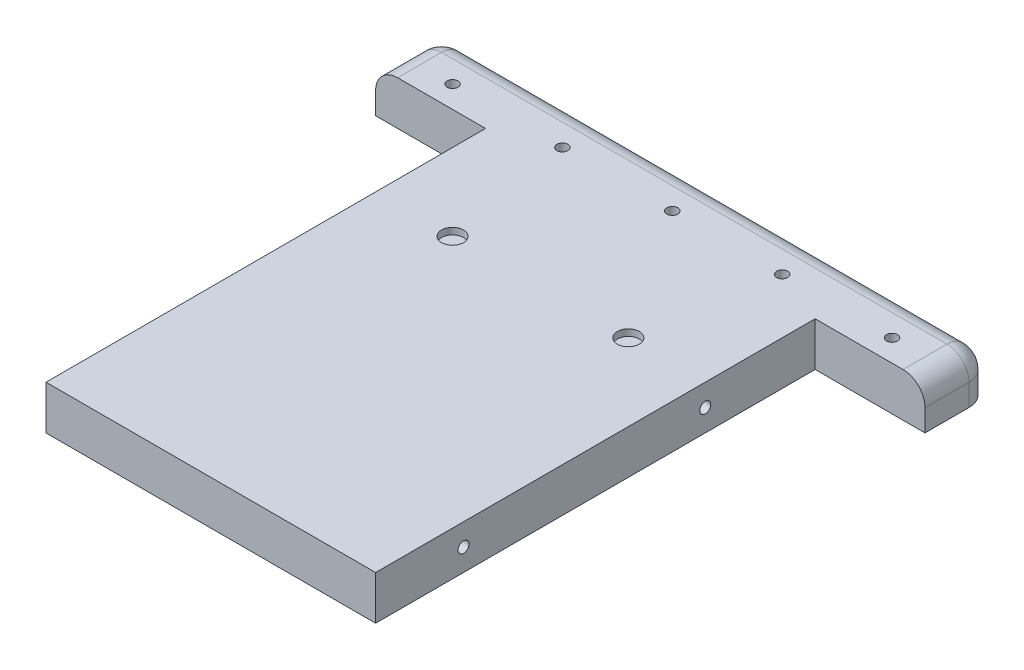
SolidWorks part; units mm, degrees
ref_plane "Front Plane" through (0, 0, 0) normal (0, 0, 1) x (1, 0, 0)
ref_plane "Top Plane" through (0, 0, 0) normal (0, 1, 0) x (1, 0, 0)
ref_plane "Right Plane" through (0, 0, 0) normal (1, 0, 0) x (0, 0, -1)
sketch "Sketch1" plane through (0, 0, 0) normal (0, 1, 0) x (1, 0, 0)
  line L0 (-75, -100) -> (75, -100)
  line L1 (75, -100) -> (75, 100)
  line L2 (75, 100) -> (125, 100)
  line L3 (125, 100) -> (125, 130)
  line L4 (125, 130) -> (-125, 130)
  line L5 (-125, 130) -> (-125, 100)
  line L6 (-125, 100) -> (-75, 100)
  line L7 (-75, 100) -> (-75, -100)
  point P7 (0, -100)
  point P9 (-75, 0)
  dimension "D1" = 250
  dimension "D2" = 30
  dimension "D3" = 150
  dimension "D4" = 200
extrude "Boss-Extrude1" add sketch "Sketch1" along normal blind 20
sketch "Sketch2" plane through (-75, 0, 0) normal (-1, 0, 0) x (0, 0, 1)
  line L0 (100, 20) -> (100, 0) construction
  circle A0 centre (60, 10) radius 2.5
  circle A1 centre (-50, 10) radius 2.5
  point P6 (100, 10)
  dimension "D1" = 5
  dimension "D2" = 40
  dimension "D3" = 110
extrude "Cut-Extrude1" cut sketch "Sketch2" against normal through all
sketch "Sketch4" plane through (0, 0, 0) normal (0, -1, 0) x (1, 0, 0)
  line L0 (-125, -115) -> (125, -115) construction
  line L1 (-125, -130) -> (-125, -100) construction
  line L2 (125, -100) -> (125, -130) construction
  line L3 (0, -11) -> (0, 11) construction
  circle A0 centre (-100, -115) radius 2.5
  circle A1 centre (-50, -115) radius 2.5
  circle A2 centre (0, -115) radius 2.5
  circle A3 centre (50, -115) radius 2.5
  circle A4 centre (100, -115) radius 2.5
  dimension "D1" = 5
  dimension "D2" = 25
  dimension "D3" = 50
extrude "Cut-Extrude2" cut sketch "Sketch4" against normal blind 5
fillet "Fillet1" radius 10 2 edges at (125, 10, -130) (-125, 10, -130)
fillet "Fillet2" radius 10 5 edges at (125, 20, -110) (122.0711, 20, -127.0711) (-125, 20, -110) (-122.0711, 20, -127.0711) (0, 20, -130)
sketch "Sketch6" plane through (0, 20, 0) normal (0, 1, 0) x (1, 0, 0)
  line L0 (115, 110) -> (-115, 110) construction
  line L1 (115, 100) -> (115, 120) construction
  line L2 (-115, 120) -> (-115, 100) construction
  line L3 (0, -11) -> (0, 11) construction
  circle A0 centre (0, 110) radius 2.5
  circle A1 centre (50, 110) radius 2.5
  circle A2 centre (100, 110) radius 2.5
  circle A3 centre (-50, 110) radius 2.5
  circle A4 centre (-100, 110) radius 2.5
  dimension "D1" = 5
  dimension "D2" = 50
  dimension "D3" = 50
extrude "Cut-Extrude3" cut sketch "Sketch6" against normal blind 5
sketch "Sketch8" plane through (0, 20, 0) normal (0, 1, 0) x (1, 0, 0)
  line L0 (-75, 100) -> (-75, -100) construction
  line L1 (-75, -100) -> (75, -100) construction
  line L2 (0, -11) -> (0, 11) construction
  circle A0 centre (-40, 50) radius 5
  circle A1 centre (40, 50) radius 5
  dimension "D1" = 10
  dimension "D2" = 35
  dimension "D3" = 150
extrude "Cut-Extrude5" cut sketch "Sketch8" against normal blind 3
ref_plane "Plane1" through (0, 10, 0) normal (0, 1, 0) x (1, 0, 0)
sketch "Sketch10" plane through (0, 10, 0) normal (0, 1, 0) x (1, 0, 0)
  line L0 (75, -62.5) -> (75, -57.5) construction
  line L1 (-75, -57.5) -> (-75, -62.5) construction
  line L2 (75, -62.5) -> (75, -57.5) construction
  line L3 (-75, -57.5) -> (-75, -62.5) construction
  line L4 (-75, -60) -> (75, -60) construction
  line L5 (75, 47.5) -> (75, 52.5) construction
  line L6 (-75, 52.5) -> (-75, 47.5) construction
  line L7 (75, 47.5) -> (75, 52.5) construction
  line L8 (-75, 52.5) -> (-75, 47.5) construction
  line L9 (-75, 50) -> (75, 50) construction
  point P12 (0, -60)
  point P13 (0, 50)
